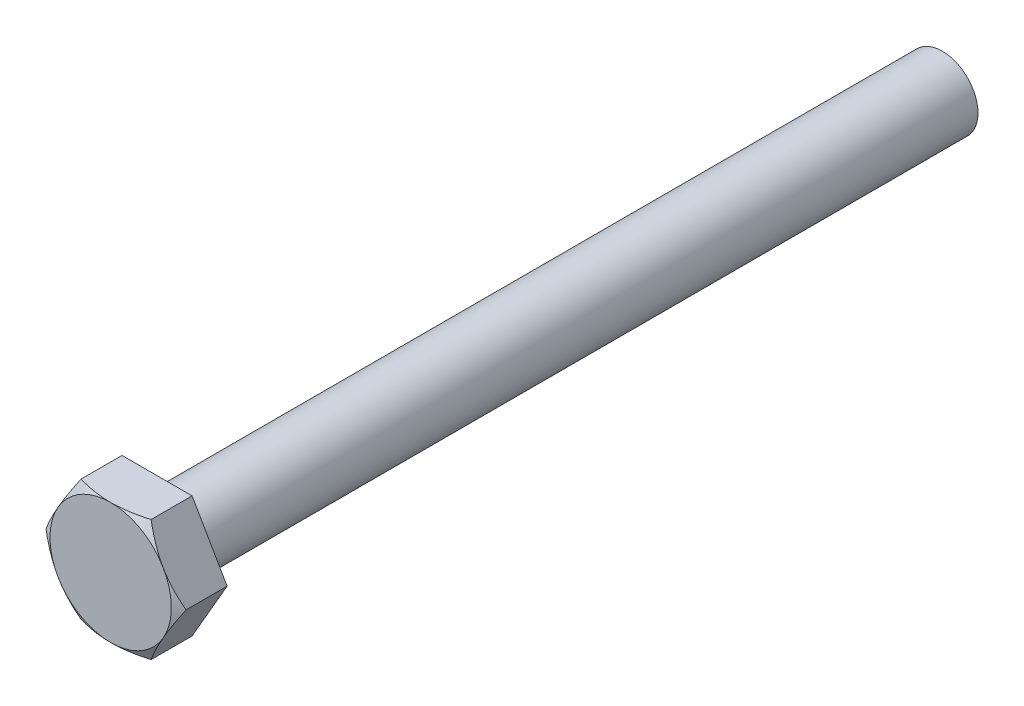
SolidWorks part; units mm, degrees
ref_plane "Front Plane" through (0, 0, 0) normal (0, 0, 1) x (1, 0, 0)
ref_plane "Top Plane" through (0, 0, 0) normal (0, 1, 0) x (1, 0, 0)
ref_plane "Right Plane" through (0, 0, 0) normal (1, 0, 0) x (0, 0, -1)
sketch "Sketch1" plane through (0, 0, 0) normal (0, 0, 1) x (1, 0, 0)
  circle A0 centre (0, 0) radius 10
  dimension "D1" = 20
extrude "Boss-Extrude1" add sketch "Sketch1" along normal mid plane 220
cosmetic thread "Cosmetic Thread1" parameters "D1"=15, "D2"=17.252
sketch "Sketch2" plane through (0, 0, 110) normal (0, 0, 1) x (1, 0, 0)
  line L1 (-19.6299, 0) -> (-9.815, -17)
  line L2 (-9.815, -17) -> (9.815, -17)
  line L3 (9.815, -17) -> (19.6299, 0)
  line L4 (19.6299, 0) -> (9.815, 17)
  line L5 (9.815, 17) -> (-9.815, 17)
  line L6 (-9.815, 17) -> (-19.6299, 0)
  circle A0 centre (0, 0) radius 17 construction
  point P1 (0, 0)
  dimension "D1" = 34
  dimension "D2" = 19.6299
extrude "Boss-Extrude2" add sketch "Sketch2" along normal blind 13
sketch "Sketch3" plane through (0, 0, 123) normal (0, 0, 1) x (1, 0, 0)
  circle A0 centre (0, 0) radius 17
extrude "Cut-Extrude1" cut sketch "Sketch3" against normal blind 13 draft 60 flip side to cut
